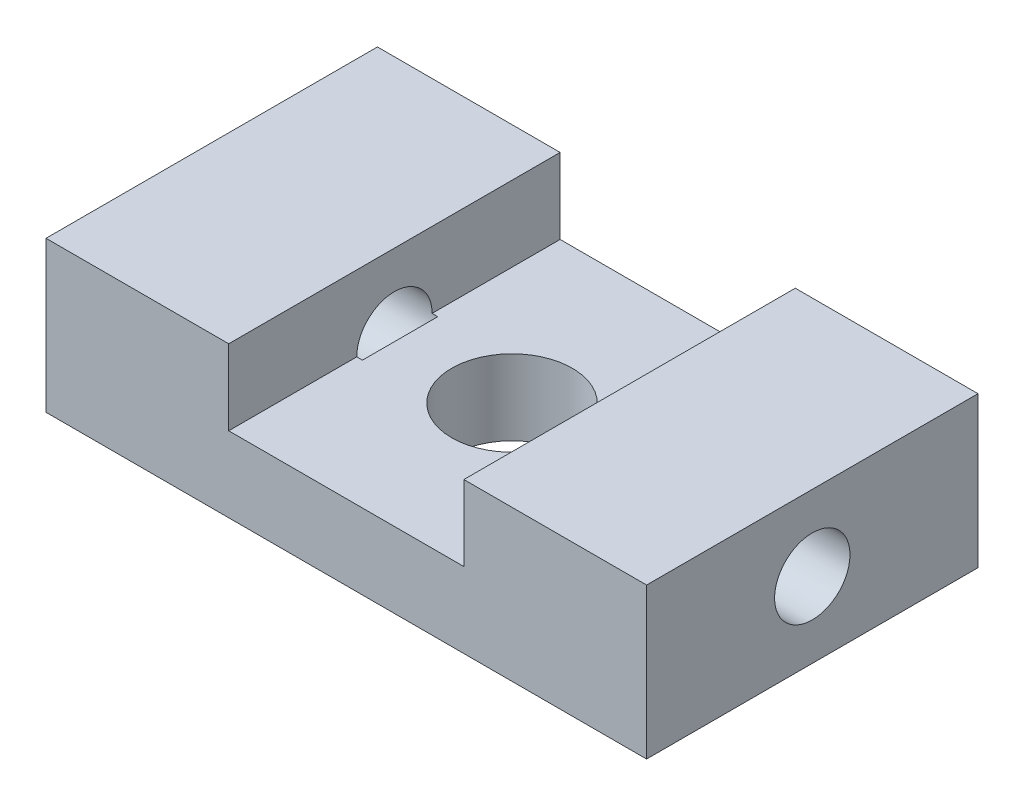
SolidWorks part; units mm, degrees
ref_plane "Спереди" through (0, 0, 0) normal (0, 0, 1) x (1, 0, 0)
ref_plane "Сверху" through (0, 0, 0) normal (0, 1, 0) x (1, 0, 0)
ref_plane "Справа" through (0, 0, 0) normal (1, 0, 0) x (0, 0, -1)
sketch "Эскиз1" plane through (0, 0, 0) normal (0, 1, 0) x (1, 0, 0)
  line L1 (-39.8443, 21.987) -> (39.8443, 21.987)
  line L2 (-39.8443, 21.987) -> (-39.8443, -21.987)
  line L3 (-39.8443, -21.987) -> (39.8443, -21.987)
  line L4 (39.8443, 21.987) -> (39.8443, -21.987)
  line L5 (-39.8443, 21.987) -> (39.8443, -21.987) construction
  line L6 (-39.8443, -21.987) -> (39.8443, 21.987) construction
  circle A0 centre (0, 0) radius 8
  point P0 (0, 0)
extrude "Вытянуть1" add sketch "Эскиз1" along normal blind 20
sketch "Эскиз2" plane through (-39.8443, 0, 0) normal (-1, 0, 0) x (0, 0, 1)
  line L0 (-21.987, 0) -> (21.987, 20) construction
  line L1 (-21.987, 20) -> (21.987, 0) construction
  circle A0 centre (0, 10) radius 5
extrude "Вытянуть2" cut sketch "Эскиз2" against normal blind 25
sketch "Эскиз3" plane through (39.8443, 0, 0) normal (1, 0, 0) x (0, 0, -1)
  line L0 (-21.987, 0) -> (21.987, 20) construction
  line L1 (-21.987, 20) -> (21.987, 0) construction
  circle A0 centre (0, 10) radius 5
extrude "Вытянуть3" cut sketch "Эскиз3" against normal blind 25
sketch "Эскиз4" plane through (0, 20, 0) normal (0, 1, 0) x (1, 0, 0)
  line L0 (0, 21.987) -> (0, 29.9461) construction
  line L3 (-15.6, 25) -> (15.6, 25)
  line L4 (-15.6, 25) -> (-15.6, -25)
  line L5 (-15.6, -25) -> (15.6, -25)
  line L6 (15.6, 25) -> (15.6, -25)
  line L7 (-15.6, 25) -> (15.6, -25) construction
  line L8 (-15.6, -25) -> (15.6, 25) construction
  point P1 (0, 0)
extrude "Вытянуть4" cut sketch "Эскиз4" against normal blind 10
